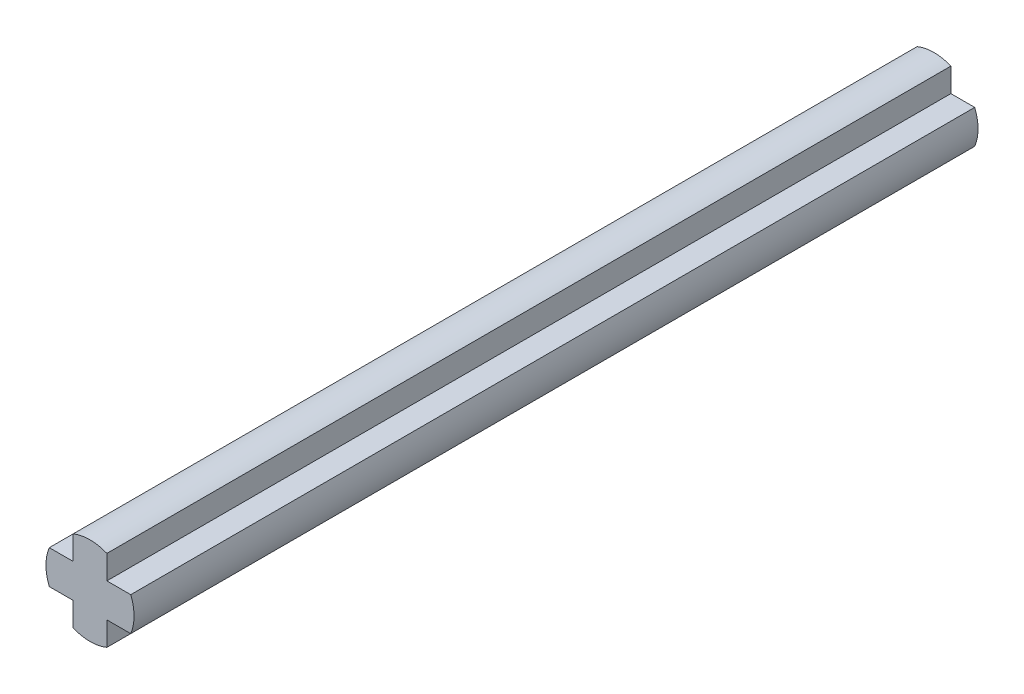
SolidWorks part; units mm, degrees
ref_plane "Front Plane" through (0, 0, 0) normal (0, 0, 1) x (1, 0, 0)
ref_plane "Top Plane" through (0, 0, 0) normal (0, 1, 0) x (1, 0, 0)
ref_plane "Right Plane" through (0, 0, 0) normal (1, 0, 0) x (0, 0, -1)
sketch "Sketch1" plane through (0, 0, 0) normal (0, 0, 1) x (1, 0, 0)
  line L0 (-0.9, 2.1708) -> (-0.9, 0.9)
  line L1 (0.9, 2.1708) -> (0.9, 0.9)
  line L2 (-2.1708, 0.9) -> (-0.9, 0.9)
  line L3 (-2.1708, -0.9) -> (-0.9, -0.9)
  line L4 (-0.9, -0.9) -> (-0.9, -2.1708)
  line L5 (0.9, 0.9) -> (2.1708, 0.9)
  line L6 (0.9, -0.9) -> (0.9, -2.1708)
  line L7 (0.9, -0.9) -> (2.1708, -0.9)
  arc A0 (-0.9, -2.1708) -> (0.9, -2.1708) centre (0, 0) ccw
  arc A1 (2.1708, -0.9) -> (2.1708, 0.9) centre (0, 0) ccw
  arc A2 (0.9, 2.1708) -> (-0.9, 2.1708) centre (0, 0) ccw
  arc A3 (-2.1708, 0.9) -> (-2.1708, -0.9) centre (0, 0) ccw
  dimension "D1" = 4.7
  dimension "D2" = 0.9
  dimension "D3" = 1.8
  dimension "D4" = 0.9
  dimension "D5" = 1.8
extrude "Boss-Extrude1" add sketch "Sketch1" along normal blind 45
